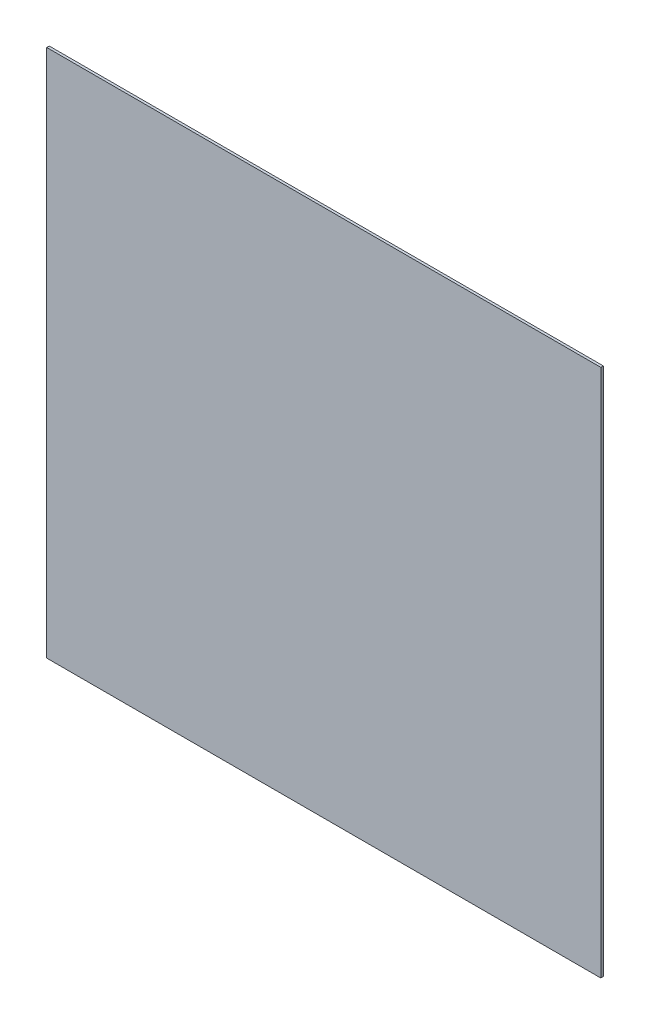
SolidWorks part; units mm, degrees
ref_plane "Plan de face" through (0, 0, 0) normal (0, 0, 1) x (1, 0, 0)
ref_plane "Plan de dessus" through (0, 0, 0) normal (0, 1, 0) x (1, 0, 0)
ref_plane "Plan de droite" through (0, 0, 0) normal (1, 0, 0) x (0, 0, -1)
sketch "Esquisse1" plane through (0, 0, 0) normal (0, 0, 1) x (1, 0, 0)
  line L0 (-339.3008, 49.1175) -> (392.424, 49.1175) construction
  line L1 (0, 213.7374) -> (0, -193.1395) construction
  line L2 (-220, 259.1175) -> (-220, -160.8825)
  line L3 (-220, -160.8825) -> (220, -160.8825)
  line L4 (220, -160.8825) -> (220, 259.1175)
  line L5 (220, 259.1175) -> (-220, 259.1175)
  point P7 (0, 0)
  point P10 (0, 0)
  point P11 (0, 0)
  dimension "D1" = 440
  dimension "D2" = 420
extrude "Boss.-Extru.1" add sketch "Esquisse1" along normal blind 2
